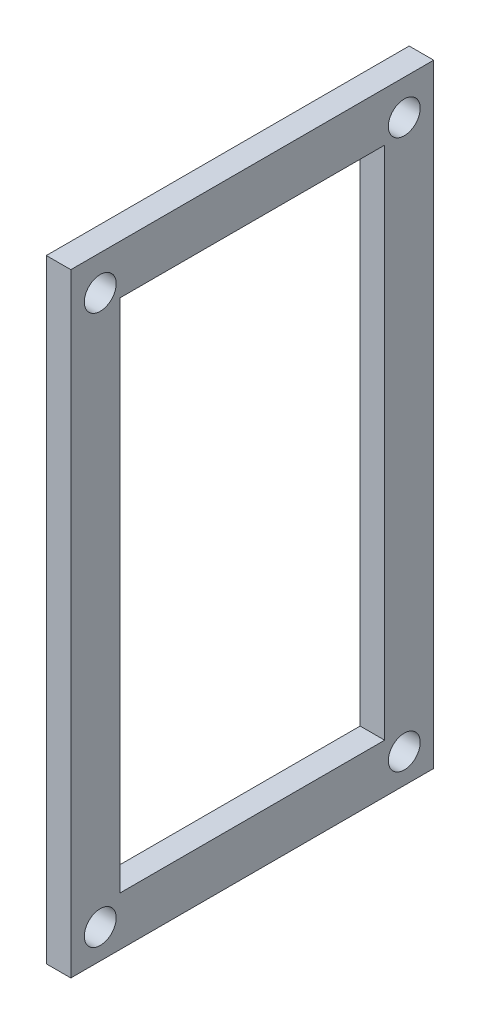
SolidWorks part; units mm, degrees
ref_plane "Front Plane" through (0, 0, 0) normal (0, 0, 1) x (1, 0, 0)
ref_plane "Top Plane" through (0, 0, 0) normal (0, 1, 0) x (1, 0, 0)
ref_plane "Right Plane" through (0, 0, 0) normal (1, 0, 0) x (0, 0, -1)
sketch "Sketch1" plane through (0, 0, 0) normal (1, 0, 0) x (0, 0, -1)
  line L0 (0, -60.55) -> (0, -49.083) construction
  line L1 (-35, 60.55) -> (35, 60.55)
  line L2 (-35, 60.55) -> (-35, -60.55)
  line L3 (-35, -60.55) -> (35, -60.55)
  line L4 (35, 60.55) -> (35, -60.55)
  line L5 (-35, 60.55) -> (35, -60.55) construction
  line L6 (-35, -60.55) -> (35, 60.55) construction
  line L7 (-27, 52.55) -> (27, 52.55)
  line L8 (-27, 52.55) -> (-27, -52.55)
  line L9 (-27, -52.55) -> (27, -52.55)
  line L10 (27, 52.55) -> (27, -52.55)
  line L11 (-27, 52.55) -> (27, -52.55) construction
  line L12 (-27, -52.55) -> (27, 52.55) construction
  circle A0 centre (-31, -56.55) radius 3.25
  circle A1 centre (31, -56.55) radius 3.25
  circle A2 centre (-31, 55.45) radius 3.25
  circle A3 centre (31, 55.45) radius 3.25
  point P0 (0, 0)
  point P6 (0, 0)
  dimension "D5" = 6.5
  dimension "D6" = 4
  dimension "D7" = 4
  dimension "D8" = 6.5
  dimension "D9" = 5.1
  dimension "D10" = 4
  dimension "D1" = 121.1
  dimension "D2" = 70
  dimension "D3" = 54
  dimension "D4" = 105.1
extrude "Boss-Extrude1" add sketch "Sketch1" along normal blind 5
sketch "Sketch2" plane through (0, 0, 35) normal (0, 0, 1) x (1, 0, 0)
  line L4 (0, 60.55) -> (0, -60.55)
  line L5 (0, -60.55) -> (5, -60.55)
  line L6 (5, -60.55) -> (5, 60.55)
  line L7 (5, 60.55) -> (0, 60.55)
  line L8 (0, 60.55) -> (0, -60.55)
  line L9 (0, -60.55) -> (5, -60.55)
  line L10 (5, -60.55) -> (5, 60.55)
  line L11 (5, 60.55) -> (0, 60.55)
  dimension "D1" = 0
extrude "Boss-Extrude2" add sketch "Sketch2" along normal blind 2
sketch "Sketch3" plane through (0, 60.55, 0) normal (0, 1, 0) x (1, 0, 0)
  line L4 (0, 35) -> (0, -37)
  line L5 (0, -37) -> (5, -37)
  line L6 (5, -37) -> (5, 35)
  line L7 (5, 35) -> (0, 35)
  line L8 (0, 35) -> (0, -37)
  line L9 (0, -37) -> (5, -37)
  line L10 (5, -37) -> (5, 35)
  line L11 (5, 35) -> (0, 35)
  dimension "D1" = 0
extrude "Boss-Extrude3" add sketch "Sketch3" along normal blind 2
sketch "Sketch4" plane through (0, 0, -35) normal (0, 0, -1) x (-1, 0, 0)
  line L4 (0, -60.55) -> (0, 62.55)
  line L5 (0, 62.55) -> (-5, 62.55)
  line L6 (-5, 62.55) -> (-5, -60.55)
  line L7 (-5, -60.55) -> (0, -60.55)
  line L8 (0, -60.55) -> (0, 62.55)
  line L9 (0, 62.55) -> (-5, 62.55)
  line L10 (-5, 62.55) -> (-5, -60.55)
  line L11 (-5, -60.55) -> (0, -60.55)
  dimension "D1" = 0
extrude "Boss-Extrude4" add sketch "Sketch4" along normal blind 2
sketch "Sketch5" plane through (0, -60.55, 0) normal (0, -1, 0) x (1, 0, 0)
  line L4 (0, 37) -> (0, -37)
  line L5 (0, -37) -> (5, -37)
  line L6 (5, -37) -> (5, 37)
  line L7 (5, 37) -> (0, 37)
  line L8 (0, 37) -> (0, -37)
  line L9 (0, -37) -> (5, -37)
  line L10 (5, -37) -> (5, 37)
  line L11 (5, 37) -> (0, 37)
  dimension "D1" = 0
extrude "Boss-Extrude5" add sketch "Sketch5" along normal blind 2
